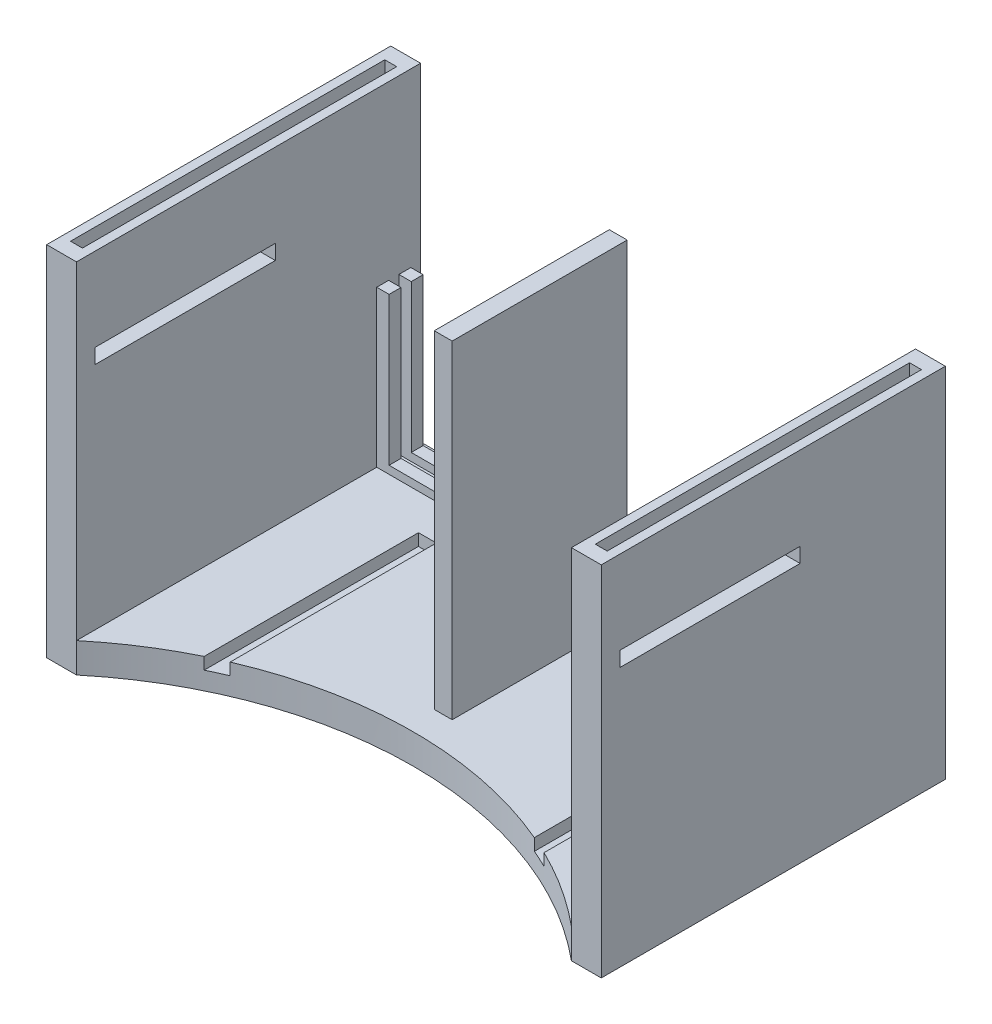
SolidWorks part; units mm, degrees
ref_plane "Front Plane" through (0, 0, 0) normal (0, 0, 1) x (1, 0, 0)
ref_plane "Top Plane" through (0, 0, 0) normal (0, 1, 0) x (1, 0, 0)
ref_plane "Right Plane" through (0, 0, 0) normal (1, 0, 0) x (0, 0, -1)
sketch "Sketch2" plane through (0, 0, 0) normal (0, 0, 1) x (1, 0, 0)
  line L0 (0, 0) -> (186, 0)
  line L1 (186, 0) -> (186, 120)
  line L2 (0, 0) -> (0, 120)
  dimension "D1" = 120
  dimension "D2" = 186
extrude "Extrude-Thin2" add sketch "Sketch2" along normal blind 115.4 thin thin type one direction wall 10
sketch "Sketch11" plane through (0, 10, 0) normal (0, 1, 0) x (1, 0, 0)
  line L0 (10, -115.4) -> (10, 0) construction
  line L1 (10, -10.703) -> (176, -10.703)
  line L2 (10, -10.703) -> (10, -14.703)
  line L3 (10, -14.703) -> (176, -14.703)
  line L4 (176, -10.703) -> (176, -14.703)
  line L6 (176, 0) -> (10, 0) construction
  dimension "D1" = 10.703
  dimension "D2" = 4
  dimension "D3" = 166
  dimension "D4" = 0
extrude "Boss-Extrude3" add sketch "Sketch11" along normal blind 2.6416
sketch "Sketch13" plane through (10, 0, 0) normal (1, 0, 0) x (0, 0, -1)
  line L0 (0, 120) -> (0, 0) construction
  line L1 (-109.195, 92.0516) -> (-48.7, 92.0516)
  line L2 (-109.195, 92.0516) -> (-109.195, 87.0516)
  line L3 (-109.195, 87.0516) -> (-48.7, 87.0516)
  line L4 (-48.7, 92.0516) -> (-48.7, 87.0516)
  line L6 (-115.4, 120) -> (-115.4, 0) construction
  line L7 (-115.4, 120) -> (0, 120) construction
  dimension "D1" = 5
  dimension "D2" = 6.205
  dimension "D3" = 48.7
  dimension "D4" = 27.9484
extrude "Cut-Extrude6" cut sketch "Sketch13" against normal through all both and the other way through all
sketch "Sketch14" plane through (0, 10, 0) normal (0, 1, 0) x (1, 0, 0)
  line L0 (176, -115.4) -> (10, -115.4)
  line L1 (93, -85.4) -> (10, -85.4) construction
  line L2 (10, -115.4) -> (10, -14.703) construction
  arc A0 (10, -115.4) -> (176, -115.4) centre (93, -215.2167) cw
  dimension "D1" = 30
extrude "Cut-Extrude7" cut sketch "Sketch14" against normal through all
sketch "Sketch19" plane through (0, 120, 0) normal (0, 1, 0) x (1, 0, 0)
  line L0 (10, -115.4) -> (10, -14.703) construction
  line L1 (3, -5) -> (7, -5)
  line L2 (3, -5) -> (3, -110.4)
  line L3 (3, -110.4) -> (7, -110.4)
  line L4 (7, -5) -> (7, -110.4)
  line L5 (0, -115.4) -> (0, 0) construction
  line L6 (0, 0) -> (10, 0) construction
  line L7 (0, -115.4) -> (10, -115.4) construction
  point P9 (5, 0)
  point P12 (5, -115.4)
  dimension "D1" = 3
  dimension "D2" = 3
  dimension "D3" = 5
  dimension "D4" = 5
extrude "Cut-Extrude9" cut sketch "Sketch19" against normal blind 10
sketch "Sketch20" plane through (0, 120, 0) normal (0, 1, 0) x (1, 0, 0)
  line L0 (186, -115.4) -> (186, 0) construction
  line L1 (179, -5) -> (183, -5)
  line L2 (179, -5) -> (179, -110.4)
  line L3 (179, -110.4) -> (183, -110.4)
  line L4 (183, -5) -> (183, -110.4)
  line L5 (176, -115.4) -> (176, 0) construction
  line L6 (176, 0) -> (186, 0) construction
  line L7 (176, -115.4) -> (186, -115.4) construction
  point P9 (181, 0)
  point P12 (181, -115.4)
  dimension "D1" = 3
  dimension "D2" = 3
  dimension "D3" = 5
  dimension "D4" = 5
extrude "Cut-Extrude10" cut sketch "Sketch20" against normal blind 10
sketch "Sketch21" plane through (0, 10, 0) normal (0, 1, 0) x (1, 0, 0)
  line L0 (176, -115.4) -> (176, -14.703) construction
  line L1 (90, -16.703) -> (96, -16.703)
  line L2 (90, -16.703) -> (90, -75.4)
  line L3 (90, -75.4) -> (96, -75.4)
  line L4 (96, -16.703) -> (96, -75.4)
  line L5 (10, -115.4) -> (10, 0) construction
  line L7 (10, -109.195) -> (10, -48.7) construction
  line L8 (10, -69.195) -> (176, -69.195) construction
  line L9 (10, -115.4) -> (10, -14.703) construction
  line L10 (0, -115.4) -> (10, -115.4) construction
  line L11 (10, -14.703) -> (176, -14.703) construction
  dimension "D1" = 80
  dimension "D2" = 80
  dimension "D3" = 40
  dimension "D4" = 46.205
  dimension "D5" = 2
extrude "Boss-Extrude4" add sketch "Sketch21" along direction (0, 1, 0) on the side of the normal through all
sketch "Sketch22" plane through (0, 10, 0) normal (0, 1, 0) x (1, 0, 0)
  line L0 (36, -26.703) -> (36, -98.5832)
  line L1 (36, -98.5832) -> (42, -95.8376)
  line L2 (42, -95.8376) -> (42, -26.703)
  line L3 (42, -26.703) -> (36, -26.703)
  line L4 (10, -14.703) -> (176, -14.703) construction
  line L6 (10, -109.195) -> (10, -48.7) construction
  line L7 (144, -95.8376) -> (150, -98.5832)
  line L8 (150, -98.5832) -> (150, -26.703)
  line L9 (150, -26.703) -> (144, -26.703)
  line L10 (144, -26.703) -> (144, -95.8376)
  line L11 (176, -115.4) -> (176, -14.703) construction
  arc A0 (176, -115.4) -> (10, -115.4) centre (93, -215.2167) ccw construction
  dimension "D1" = 6
  dimension "D2" = 26
  dimension "D3" = 6
  dimension "D4" = 26
  dimension "D5" = 12
extrude "Cut-Extrude11" cut sketch "Sketch22" against normal blind 4
sketch "Sketch23" plane through (0, 10, 0) normal (0, 1, 0) x (1, 0, 0)
  line L0 (10, -10.703) -> (10, 0) construction
  line L1 (10, -3.263) -> (176, -3.263)
  line L2 (10, -3.263) -> (10, -7.263)
  line L3 (10, -7.263) -> (176, -7.263)
  line L4 (176, -3.263) -> (176, -7.263)
  line L8 (176, -10.703) -> (10, -10.703) construction
  dimension "D1" = 3.44
  dimension "D2" = 166
  dimension "D3" = 0
  dimension "D4" = 4
extrude "Boss-Extrude5" add sketch "Sketch23" along normal blind 2.6416
sketch "Sketch24" plane through (0, 12.6416, 0) normal (0, 1, 0) x (1, 0, 0)
  line L0 (10, -7.263) -> (176, -7.263) construction
  line L1 (10, -3.263) -> (14.14, -3.263)
  line L2 (10, -3.263) -> (10, -7.263)
  line L3 (10, -7.263) -> (14.14, -7.263)
  line L4 (14.14, -3.263) -> (14.14, -7.263)
  dimension "D1" = 4.14
extrude "Boss-Extrude6" add sketch "Sketch24" along normal blind 49.64
sketch "Sketch25" plane through (0, 12.6416, 0) normal (0, 1, 0) x (1, 0, 0)
  line L0 (14.14, -7.263) -> (176, -7.263) construction
  line L1 (176, -3.263) -> (171.86, -3.263)
  line L2 (176, -3.263) -> (176, -7.263)
  line L3 (176, -7.263) -> (171.86, -7.263)
  line L4 (171.86, -3.263) -> (171.86, -7.263)
  dimension "D1" = 4.14
extrude "Boss-Extrude7" add sketch "Sketch25" along normal blind 49.64
sketch "Sketch26" plane through (0, 12.6416, 0) normal (0, 1, 0) x (1, 0, 0)
  line L0 (10, -14.703) -> (176, -14.703) construction
  line L1 (10, -10.703) -> (14.14, -10.703)
  line L2 (10, -10.703) -> (10, -14.703)
  line L3 (10, -14.703) -> (14.14, -14.703)
  line L4 (14.14, -10.703) -> (14.14, -14.703)
  dimension "D1" = 4.14
extrude "Boss-Extrude8" add sketch "Sketch26" along normal blind 49.64
sketch "Sketch27" plane through (0, 12.6416, 0) normal (0, 1, 0) x (1, 0, 0)
  line L0 (14.14, -14.703) -> (176, -14.703) construction
  line L1 (176, -10.703) -> (171.86, -10.703)
  line L2 (176, -10.703) -> (176, -14.703)
  line L3 (176, -14.703) -> (171.86, -14.703)
  line L4 (171.86, -10.703) -> (171.86, -14.703)
  dimension "D1" = 4.14
extrude "Boss-Extrude9" add sketch "Sketch27" along normal blind 49.64
